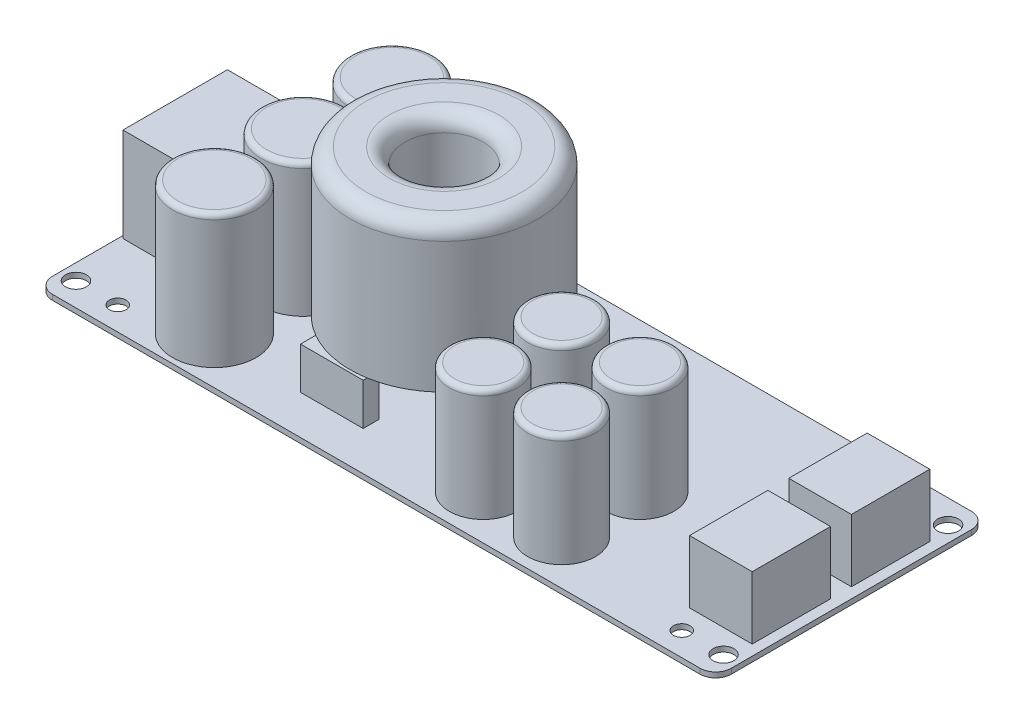
SolidWorks part; units mm, degrees
ref_plane "前视基准面" through (0, 0, 0) normal (0, 0, 1) x (1, 0, 0)
ref_plane "上视基准面" through (0, 0, 0) normal (0, 1, 0) x (1, 0, 0)
ref_plane "右视基准面" through (0, 0, 0) normal (1, 0, 0) x (0, 0, -1)
sketch "Sketch1" plane through (0, 0, 0) normal (0, 1, 0) x (1, 0, 0)
  line L1 (-62, 26) -> (62, 26)
  line L2 (-65, 23) -> (-65, -23)
  line L3 (-62, -26) -> (62, -26)
  line L4 (65, 23) -> (65, -23)
  line L5 (-65, 26) -> (65, -26) construction
  line L6 (-65, -26) -> (65, 26) construction
  arc A0 (62, 26) -> (65, 23) centre (62, 23) cw
  arc A1 (62, -26) -> (65, -23) centre (62, -23) ccw
  arc A2 (-65, -23) -> (-62, -26) centre (-62, -23) ccw
  arc A3 (-62, 26) -> (-65, 23) centre (-62, 23) ccw
  point P0 (0, 0)
  dimension "D3" = 3
  dimension "D1" = 52
  dimension "D2" = 130
extrude "Boss-Extrude1" add sketch "Sketch1" along normal blind 1
sketch "Sketch2" plane through (0, 1, 0) normal (0, 1, 0) x (1, 0, 0)
  line L1 (-62, 21.5) -> (62, 21.5) construction
  line L2 (-62, 21.5) -> (-62, -21.5) construction
  line L3 (-62, -21.5) -> (62, -21.5) construction
  line L4 (62, 21.5) -> (62, -21.5) construction
  line L5 (-62, 21.5) -> (62, -21.5) construction
  line L6 (-62, -21.5) -> (62, 21.5) construction
  line L7 (-54, -21.5) -> (54, -21.5) construction
  line L8 (-54, -21.5) -> (-54, 21.5) construction
  line L9 (-54, 21.5) -> (54, 21.5) construction
  line L10 (54, -21.5) -> (54, 21.5) construction
  line L11 (-54, -21.5) -> (54, 21.5) construction
  line L12 (-54, 21.5) -> (54, -21.5) construction
  circle A0 centre (-62, 21.5) radius 2
  circle A1 centre (-62, -21.5) radius 2
  circle A2 centre (62, -21.5) radius 2
  circle A3 centre (62, 21.5) radius 2
  circle A4 centre (-54, -21.5) radius 1.6
  circle A5 centre (-54, 21.5) radius 1.6
  circle A6 centre (54, 21.5) radius 1.6
  circle A7 centre (54, -21.5) radius 1.6
  point P0 (0, 0)
  point P10 (0, 0)
  dimension "D3" = 4
  dimension "D5" = 3.2
  dimension "D1" = 43
  dimension "D2" = 124
  dimension "D4" = 108
extrude "Cut-Extrude1" cut sketch "Sketch2" against normal up to next
sketch "Sketch3" plane through (0, 1, 0) normal (0, 1, 0) x (1, 0, 0)
  line L0 (-65, 23) -> (-65, -23) construction
  circle A0 centre (-40, 17) radius 8
  circle A1 centre (-40, 0) radius 8
  circle A2 centre (-40, -17) radius 8
  dimension "D2" = 16
  dimension "D1" = 25
  dimension "D3" = 17
  dimension "D4" = 17
extrude "Boss-Extrude2" add sketch "Sketch3" along normal blind 25.5
sketch "Sketch4" plane through (0, 1, 0) normal (0, 1, 0) x (1, 0, 0)
  line L0 (65, -23) -> (65, 23) construction
  line L1 (-62, -26) -> (62, -26) construction
  circle A0 centre (12, -17.5) radius 6.5
  circle A1 centre (12, -2.5) radius 6.5
  circle A2 centre (27, -2.5) radius 6.5
  circle A3 centre (27, -17.5) radius 6.5
  point P8 (0, 0)
  point P9 (0, 0)
  point P10 (0, 0)
  point P11 (0, 0)
  dimension "D1" = 13
  dimension "D2" = 15
  dimension "D3" = 15
  dimension "D4" = 38
  dimension "D5" = 8.5
extrude "Boss-Extrude3" add sketch "Sketch4" along normal blind 21.5
sketch "Sketch5" plane through (0, 1, 0) normal (0, 1, 0) x (1, 0, 0)
  line L0 (-62, -26) -> (62, -26) construction
  line L1 (-22, -15.5) -> (-10, -15.5)
  line L2 (-22, -15.5) -> (-22, -18.5)
  line L3 (-22, -18.5) -> (-10, -18.5)
  line L4 (-10, -15.5) -> (-10, -18.5)
  line L5 (-22, -15.5) -> (-10, -18.5) construction
  line L6 (-22, -18.5) -> (-10, -15.5) construction
  line L7 (-65, 23) -> (-65, -23) construction
  point P0 (-16, -17)
  dimension "D1" = 12
  dimension "D2" = 3
  dimension "D3" = 9
  dimension "D4" = 43
extrude "Boss-Extrude4" add sketch "Sketch5" along normal blind 8
sketch "Sketch6" plane through (0, 9, 0) normal (0, 1, 0) x (1, 0, 0)
  line L0 (-65, 23) -> (-65, -23) construction
  circle A0 centre (-13, 0) radius 18
  dimension "D1" = 52
  dimension "D2" = 36
extrude "Boss-Extrude5" add sketch "Sketch6" along normal blind 28
sketch "Sketch7" plane through (0, 37, 0) normal (0, 1, 0) x (1, 0, 0)
  circle A0 centre (-13, 0) radius 7.5
  dimension "D1" = 15
extrude "Cut-Extrude2" cut sketch "Sketch7" against normal up to next
sketch "Sketch8" plane through (0, 1, 0) normal (0, 1, 0) x (1, 0, 0)
  line L1 (-64.5, 10) -> (-48.5, 10)
  line L2 (-64.5, 10) -> (-64.5, -10)
  line L3 (-64.5, -10) -> (-48.5, -10)
  line L4 (-48.5, 10) -> (-48.5, -10)
  line L5 (-65, 23) -> (-65, -23) construction
  point P4 (-62.9716, -10)
  point P6 (-48.5, 0)
  dimension "D1" = 20
  dimension "D2" = 16
  dimension "D3" = 0.5
extrude "Boss-Extrude6" add sketch "Sketch8" along normal blind 18
sketch "Sketch9" plane through (0, 1, 0) normal (0, 1, 0) x (1, 0, 0)
  line L0 (63, 2) -> (63, -2) construction
  line L1 (63, -17) -> (51, -17)
  line L2 (63, -17) -> (63, -2)
  line L3 (63, -2) -> (51, -2)
  line L4 (51, -17) -> (51, -2)
  line L5 (63, 2) -> (51, 2)
  line L6 (63, 2) -> (63, 17)
  line L7 (63, 17) -> (51, 17)
  line L8 (51, 2) -> (51, 17)
  line L9 (65, -23) -> (65, 23) construction
  point P8 (63, 0)
  dimension "D1" = 15
  dimension "D2" = 15
  dimension "D3" = 12
  dimension "D4" = 34
  dimension "D5" = 2
extrude "Boss-Extrude7" add sketch "Sketch9" along normal blind 12
fillet "Fillet1" radius 3 3 edges at (-13, 37, 18) (-13, 37, 7.5) (-13, 9, 7.5)
fillet "Fillet2" radius 1 7 edges at (27, 22.5, 9) (27, 22.5, 24) (12, 22.5, 24) (12, 22.5, 9) (-40, 26.5, 25) (-40, 26.5, 8) (-40, 26.5, -9)
